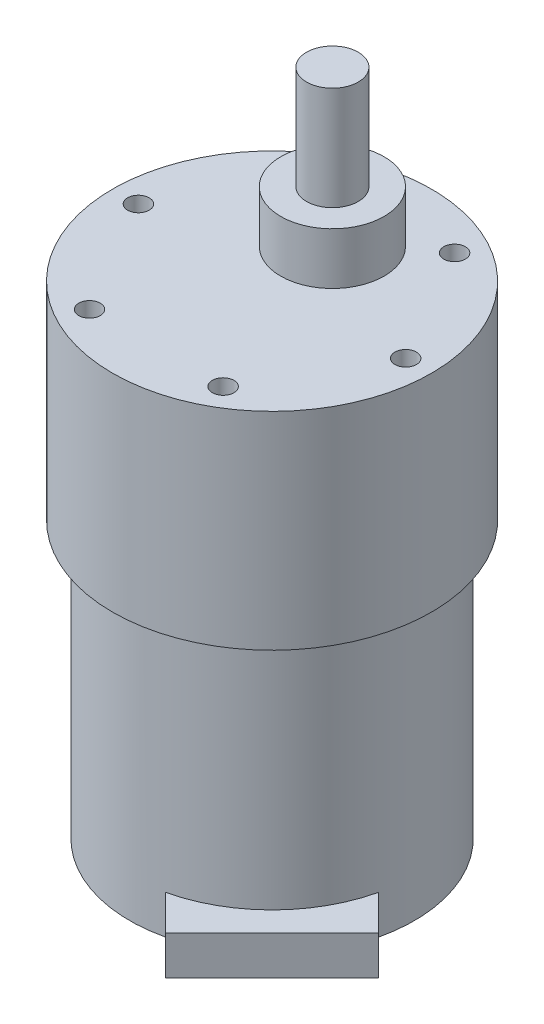
SolidWorks part; units mm, degrees
material "2024-T4"
ref_plane "前视基准面" through (0, 0, 0) normal (0, 0, 1) x (1, 0, 0)
ref_plane "上视基准面" through (0, 0, 0) normal (0, 1, 0) x (1, 0, 0)
ref_plane "右视基准面" through (0, 0, 0) normal (1, 0, 0) x (0, 0, -1)
sketch "草图1" plane through (0, 0, 0) normal (0, 1, 0) x (1, 0, 0)
  circle A0 centre (0, 0) radius 16.5
  dimension "D1" = 33
extrude "凸台-拉伸1" add sketch "草图1" along normal blind 32
sketch "草图2" plane through (0, 32, 0) normal (0, 1, 0) x (1, 0, 0)
  circle A0 centre (0, 0) radius 18.5
  dimension "D1" = 37
extrude "凸台-拉伸2" add sketch "草图2" along normal blind 24
sketch "草图3" plane through (0, 56, 0) normal (0, 1, 0) x (1, 0, 0)
  line L0 (0, 18.5) -> (0, -18.5) construction
  line L1 (-18.5, 0) -> (18.5, 0) construction
  circle A0 centre (0, 0) radius 18.5 construction
  circle A1 centre (0, 7) radius 6
  dimension "D1" = 12
  dimension "D2" = 7
extrude "凸台-拉伸3" add sketch "草图3" along normal blind 6
sketch "草图4" plane through (0, 62, 0) normal (0, 1, 0) x (1, 0, 0)
  circle A0 centre (0, 7) radius 3
  dimension "D1" = 6
extrude "凸台-拉伸4" add sketch "草图4" along normal blind 12
sketch "草图5" plane through (0, 56, 0) normal (0, 1, 0) x (1, 0, 0)
  point P0 (0, 0)
hole_wizard "M3 螺纹孔的螺纹孔钻头1" positions "草图7" profile "草图6" hole size "M3" standard "GB"
sketch "草图7" plane through (0, 56, 0) normal (0, 1, 0) x (1, 0, 0)
  line L0 (0, 0) -> (-7.75, 13.4234) construction
  line L1 (0, 18.5) -> (0, -18.5) construction
  line L3 (-18.5, 0) -> (18.5, 0) construction
  circle A0 centre (0, 0) radius 18.5 construction
  point P0 (-7.75, 13.4234)
  point P10 (7.75, 13.4234)
  point P11 (15.5, 0)
  point P12 (7.75, -13.4234)
  point P13 (-7.75, -13.4234)
  point P14 (-15.5, 0)
  dimension "D2" = 15.5
  dimension "D3" = 30
  dimension "D1" = 6
sketch "草图6" plane through (-7.75, 56, -13.4234) normal (1, 0, 0) x (0, 0, 1)
  line L0 (0, 0) -> (0, 4.0511)
  line L1 (0, 4.0511) -> (1.25, 3.3)
  line L2 (1.25, 3.3) -> (1.25, 0)
  line L5 (1.25, 0) -> (0, 0)
  line L10 (0, 4.0511) -> (-1.25, 3.3) construction
  line L11 (0, -6.35) -> (0, 107.95) construction
  dimension "孔直径" = 2.5
  dimension "孔深度" = 3.3
  dimension "导头角度" = 118
sketch "草图8" plane through (0, 0, 0) normal (0, -1, 0) x (1, 0, 0)
  line L0 (0, 16.5) -> (0, -16.5) construction
  line L1 (-16.5, 0) -> (16.5, 0) construction
  line L2 (0, 0) -> (11.6673, 11.6673) construction
  line L3 (3.7044, 16.0788) -> (16.0788, 3.7044)
  line L4 (3.7044, 16.0788) -> (7.8135, 20.1879)
  line L5 (7.8135, 20.1879) -> (20.1879, 7.8135)
  line L6 (20.1879, 7.8135) -> (16.0788, 3.7044)
  circle A0 centre (0, 0) radius 16.5 construction
  dimension "D1" = 45
  dimension "D2" = 17.5
  dimension "D3" = 3.3
extrude "凸台-拉伸5" add sketch "草图8" against normal blind 4.5
